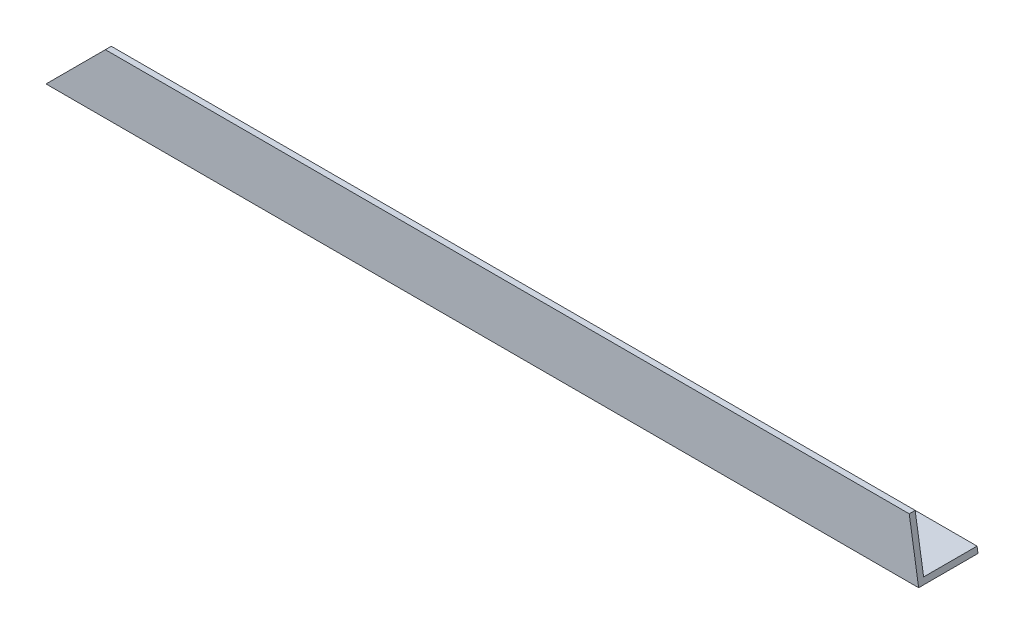
SolidWorks part; units mm, degrees
ref_plane "Front Plane" through (0, 0, 0) normal (0, 0, 1) x (1, 0, 0)
ref_plane "Top Plane" through (0, 0, 0) normal (0, 1, 0) x (1, 0, 0)
ref_plane "Right Plane" through (0, 0, 0) normal (1, 0, 0) x (0, 0, -1)
sketch "Sketch1" plane through (0, 0, 0) normal (1, 0, 0) x (0, 0, -1)
  line L0 (0, 20) -> (0, 0)
  line L1 (0, 0) -> (20, 0)
  line L2 (20, 0) -> (20, 2)
  line L3 (20, 2) -> (2, 2)
  line L4 (2, 2) -> (2, 20)
  line L5 (0, 20) -> (2, 20)
  dimension "D1" = 20
  dimension "D2" = 20
  dimension "D3" = 2
  dimension "D4" = 2
extrude "Boss-Extrude1" add sketch "Sketch1" along normal blind 294
sketch "Sketch2" plane through (0, 0, 0) normal (0, 0, -1) x (-1, 0, 0)
  line L0 (0, 0) -> (-20, 20)
  line L1 (-294, 20) -> (0, 20) construction
  line L2 (-20, 20) -> (0, 20)
  line L3 (0, 20) -> (0, 0)
  line L4 (-294, 0) -> (-290.8323, 20)
  line L5 (-290.8323, 20) -> (-294, 20)
  line L6 (-294, 20) -> (-294, 0)
  dimension "D1" = 9
  dimension "D2" = 45
extrude "Cut-Extrude1" cut sketch "Sketch2" along normal through all
